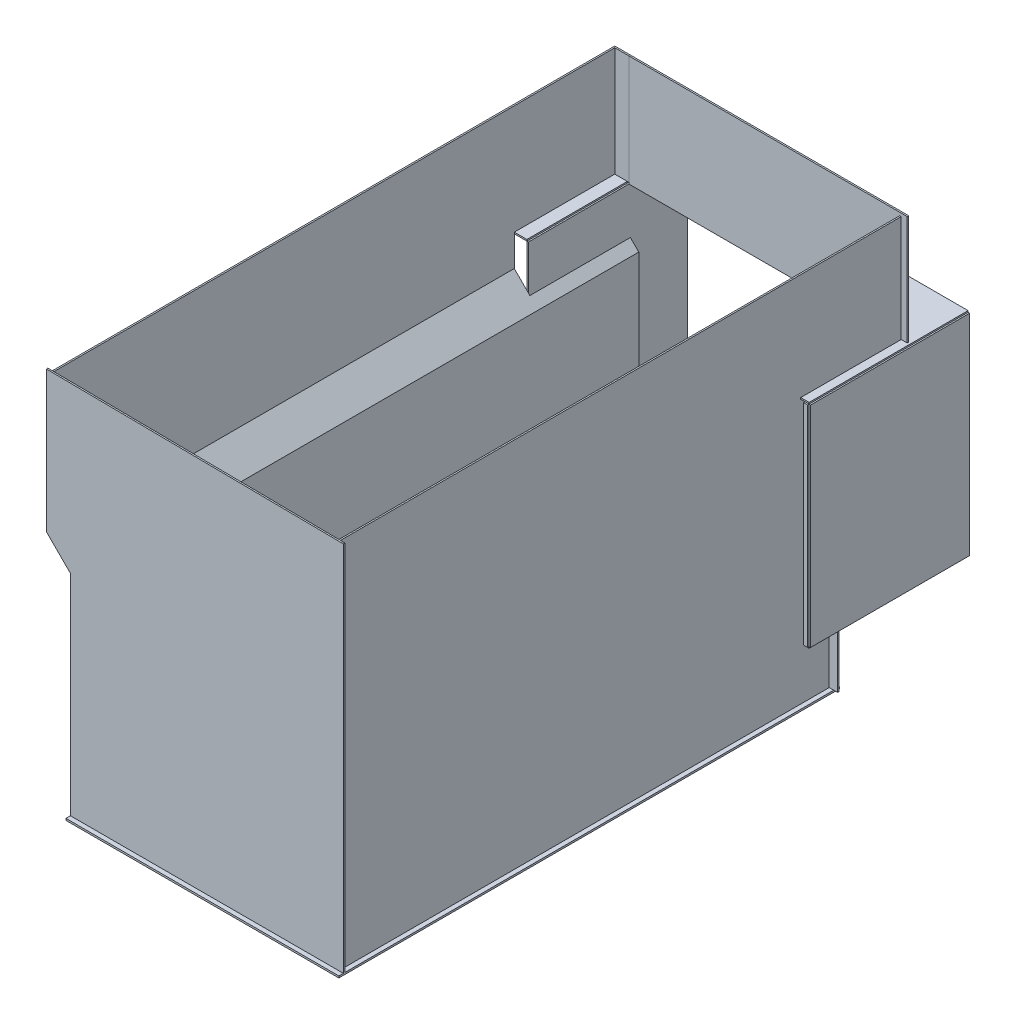
SolidWorks part; units mm, degrees
ref_plane "Front Plane" through (0, 0, 0) normal (0, 0, 1) x (1, 0, 0)
ref_plane "Top Plane" through (0, 0, 0) normal (0, 1, 0) x (1, 0, 0)
ref_plane "Right Plane" through (0, 0, 0) normal (1, 0, 0) x (0, 0, -1)
sketch "Sketch1" plane through (0, 0, 0) normal (0, 0, 1) x (1, 0, 0)
  line L0 (-2072.4189, 0) -> (1450.1392, 0) construction
  line L1 (0, 1209.3329) -> (0, -1426.529) construction
  line L9 (455, 482.6106) -> (455, -757.3894)
  line L10 (455, -757.3894) -> (-455, -757.3894)
  line L11 (-455, -757.3894) -> (-455, -57.3894)
  line L12 (-455, -57.3894) -> (-535, 22.6106)
  line L13 (-535, 22.6106) -> (-535, 492.6106)
  line L14 (-535, 492.6106) -> (455, 482.6106)
  dimension "D1" = 1240
  dimension "D2" = 1250
  dimension "D3" = 910
  dimension "D4" = 990
  dimension "D5" = 700
  dimension "D6" = 80
  dimension "D7" = 80
  dimension "D8" = 470
  dimension "D13" = 455
extrude "Boss-Extrude1" add sketch "Sketch1" along normal blind 5
sketch "Sketch2" plane through (0, -757.3894, 0) normal (0, -1, 0) x (-1, 0, 0)
  line L0 (455, -20) -> (-455, -20)
  line L1 (-455, -20) -> (-455, 1650)
  line L2 (-455, 1650) -> (455, 1650)
  line L3 (455, 1650) -> (455, -20)
  line L4 (535, -5) -> (455, -5) construction
  dimension "D1" = 910
  dimension "D2" = 455
  dimension "D3" = 1670
  dimension "D4" = 15
extrude "Boss-Extrude2" add sketch "Sketch2" along normal blind 6
sketch "Sketch3" plane through (0, 0, 0) normal (0, 0, -1) x (-1, 0, 0)
  line L2 (435, -757.3894) -> (435, -57.3894)
  line L3 (435, -57.3894) -> (515, 22.6106)
  line L4 (515, 22.6106) -> (515, 492.6106)
  line L6 (440, -757.3894) -> (440, -59.4605)
  line L7 (440, -59.4605) -> (520, 20.5395)
  line L8 (520, 20.5395) -> (520, 492.6106)
  line L9 (515, 492.6106) -> (520, 492.6106)
  line L10 (440, -757.3894) -> (435, -757.3894)
  line L12 (455, -757.3894) -> (-455, -757.3894) construction
  line L15 (-440, 482.6106) -> (-435, 482.6106)
  line L16 (-440, 482.6106) -> (-440, -757.3894)
  line L17 (-440, -757.3894) -> (-435, -757.3894)
  line L18 (-435, 482.6106) -> (-435, -757.3894)
  dimension "D1" = 5
  dimension "D2" = 1250
  dimension "D3" = 700
  dimension "D4" = 80
  dimension "D5" = 80
  dimension "D6" = 0
  dimension "D7" = 435
  dimension "D8" = 1240
  dimension "D9" = 0
  dimension "D10" = 5
  dimension "D11" = 435
extrude "Boss-Extrude3" add sketch "Sketch3" along normal blind 1870
sketch "Sketch4" plane through (0, 0, 0) normal (1, 0, 0) x (0, 0, -1)
  line L0 (1630, -757.3894) -> (1630, -577.3894)
  line L1 (1650, -757.3894) -> (0, -757.3894) construction
  line L2 (1630, -577.3894) -> (2060, -577.3894)
  line L4 (2060, 122.6106) -> (1870, 122.6106)
  line L5 (1870, 122.6106) -> (1870, 492.6106)
  line L7 (815, 588.8415) -> (815, -1128.6828) construction
  line L8 (0, -757.3894) -> (0, 482.6106) construction
  line L13 (1630, -757.3894) -> (1635, -757.3894)
  line L14 (1635, -757.3894) -> (1635, -582.3894)
  line L15 (1635, -582.3894) -> (2065, -582.3894)
  line L17 (2065, 127.6106) -> (1875, 127.6106)
  line L18 (1875, 127.6106) -> (1875, 492.6106)
  line L20 (1870, 482.6106) -> (1870, -757.3894) construction
  line L21 (1875, 492.6106) -> (1870, 492.6106)
  line L22 (1688.4853, -227.3894) -> (2285.3749, -227.3894) construction
  line L23 (1650, -757.3894) -> (0, -757.3894) construction
  line L24 (2060, 122.6106) -> (2065, 122.6106)
  line L25 (2065, 122.6106) -> (2065, 127.6106)
  line L26 (2065, -582.3894) -> (2065, -577.3894)
  line L27 (2065, -577.3894) -> (2060, -577.3894)
  dimension "D1" = 180
  dimension "D3" = 815
  dimension "D5" = 815
  dimension "D6" = 5
  dimension "D7" = 5
  dimension "D9" = 5
  dimension "D10" = 5
  dimension "D11" = 0
  dimension "D12" = 1250
  dimension "D13" = 700
  dimension "D14" = 350
  dimension "D15" = 530
extrude "Boss-Extrude4" add sketch "Sketch4" along normal mid plane 936
sketch "Sketch5" plane through (440, 0, 0) normal (1, 0, 0) x (0, 0, -1)
  line L0 (1635, -582.3894) -> (1870, -582.3894)
  line L1 (1870, -582.3894) -> (1870, -757.3894)
  line L2 (1870, -757.3894) -> (1635, -757.3894)
  line L3 (1635, -757.3894) -> (1635, -582.3894)
extrude "Cut-Extrude1" cut sketch "Sketch5" against normal through all both and the other way through all
sketch "Sketch7" plane through (468, 0, 0) normal (1, 0, 0) x (0, 0, -1)
  line L0 (2065, 122.6106) -> (1535, 122.6106)
  line L1 (1535, 122.6106) -> (1535, -577.3894)
  line L2 (2065, -577.3894) -> (1535, -577.3894)
  line L3 (1870, 482.6106) -> (1870, 122.6106) construction
  line L4 (2065, 122.6106) -> (2065, -577.3894)
  dimension "D1" = 195
  dimension "D2" = 530
  dimension "D3" = 700
extrude "Boss-Extrude5" add sketch "Sketch7" along normal blind 5 separate body
sketch "Sketch8" plane through (-468, 0, 0) normal (-1, 0, 0) x (0, 0, 1)
  line L0 (-2065, -577.3894) -> (-1535, -577.3894)
  line L1 (-1535, -577.3894) -> (-2065, -577.3894) construction
  line L2 (-1535, -577.3894) -> (-1535, 122.6106)
  line L3 (-2065, 122.6106) -> (-1535, 122.6106)
  line L4 (-1870, 492.6106) -> (-1870, 122.6106) construction
  line L5 (-1870, 20.5395) -> (-1870, 492.6106) construction
  line L6 (0, -757.3894) -> (-1630, -757.3894) construction
  line L7 (-2065, 122.6106) -> (-2065, -577.3894)
  dimension "D1" = 195
  dimension "D2" = 335
  dimension "D3" = 180
  dimension "D4" = 530
  dimension "D5" = 700
extrude "Boss-Extrude9" add sketch "Sketch8" along normal blind 5 separate body
sketch "Sketch9" plane through (-468, 0, 0) normal (-1, 0, 0) x (0, 0, 1)
  line L0 (-2065, -577.3894) -> (-1535, -577.3894) construction
  line L1 (-2065, -577.3894) -> (-1635, -577.3894)
  line L2 (-2065, -577.3894) -> (-2065, -582.3894)
  line L3 (-2065, -582.3894) -> (-1635, -582.3894)
  line L4 (-1635, -577.3894) -> (-1635, -582.3894)
  line L5 (-2065, 122.6106) -> (-2065, -577.3894) construction
  line L6 (-1635, -582.3894) -> (-2065, -582.3894) construction
  line L7 (-1635, -757.3894) -> (-1635, -582.3894) construction
extrude "Boss-Extrude12" add sketch "Sketch9" along normal blind 15 separate body
sketch "Sketch10" plane through (0, 122.6106, 0) normal (0, 1, 0) x (1, 0, 0)
  line L0 (-515, 1870) -> (-515, 0) construction
  line L1 (468, 1535) -> (440, 1535)
  line L2 (468, 1535) -> (468, 1870)
  line L3 (468, 1870) -> (440, 1870)
  line L4 (440, 1535) -> (440, 1870)
  line L5 (-515, 1870) -> (-473, 1870)
  line L6 (-515, 1870) -> (-515, 1535)
  line L7 (-515, 1535) -> (-473, 1535)
  line L8 (-473, 1870) -> (-473, 1535)
  line L9 (-515, 1870) -> (-435, 1870) construction
  dimension "D1" = 28
  dimension "D2" = 335
  dimension "D3" = 335
  dimension "D4" = 42
extrude "Boss-Extrude13" add sketch "Sketch10" along normal blind 5 separate body
sketch "Sketch11" plane through (0, 0, -1870) normal (0, 0, 1) x (1, 0, 0)
  line L0 (455, -757.3894) -> (455, 482.6106) construction
  line L1 (468, 127.6106) -> (460, 127.6106)
  line L2 (468, 127.6106) -> (468, 499.1119)
  line L3 (468, 499.1119) -> (460, 499.1119)
  line L4 (460, 127.6106) -> (460, 499.1119)
  dimension "D1" = 5
extrude "Cut-Extrude2" cut sketch "Sketch11" against normal blind 5
sketch "Sketch12" plane through (-473, 0, 0) normal (-1, 0, 0) x (0, 0, 1)
  line L0 (-1535, 122.6106) -> (-2065, 122.6106) construction
  line L1 (-1890.5162, 122.6106) -> (-1535, 122.6106)
  line L2 (-1890.5162, 122.6106) -> (-1890.5162, -41.1944)
  line L3 (-1890.5162, -41.1944) -> (-1535, -41.1944)
  line L4 (-1535, 122.6106) -> (-1535, -41.1944)
  line L5 (-1535, -577.3894) -> (-1535, 122.6106) construction
extrude "Cut-Extrude3" cut sketch "Sketch12" along normal blind 237 and the other way blind 10
sketch "Sketch13" plane through (0, 0, -1535) normal (0, 0, 1) x (1, 0, 0)
  line L0 (455, -757.3894) -> (455, 482.6106) construction
  line L1 (455, 122.6106) -> (468, 122.6106)
  line L2 (455, 122.6106) -> (455, -577.3894)
  line L3 (455, -577.3894) -> (468, -577.3894)
  line L4 (468, 122.6106) -> (468, -577.3894)
  line L5 (468, 122.6106) -> (440, 122.6106) construction
extrude "Boss-Extrude14" add sketch "Sketch13" along normal blind 5
sketch "Sketch14" plane through (0, -577.3894, 0) normal (0, -1, 0) x (-1, 0, 0)
  line L1 (-468, 1630) -> (-455, 1630)
  line L2 (-468, 1630) -> (-468, 1535)
  line L3 (-468, 1535) -> (-455, 1535)
  line L4 (-455, 1630) -> (-455, 1535)
extrude "Boss-Extrude15" add sketch "Sketch14" along normal blind 5
sketch "Sketch15" plane through (0, 0, -1535) normal (0, 0, 1) x (1, 0, 0)
  line L0 (-468, -577.3894) -> (-468, 122.6106) construction
  line L1 (-468, -577.3894) -> (-455, -577.3894)
  line L2 (-468, -577.3894) -> (-468, -57.3894)
  line L4 (-455, -577.3894) -> (-455, -57.3894)
  line L5 (-535, 22.6106) -> (-455, -57.3894) construction
  line L6 (-468, -44.3894) -> (-455, -44.3894)
  line L7 (-468, -44.3894) -> (-468, -57.3894)
  line L9 (-455, -44.3894) -> (-455, -57.3894)
extrude "Boss-Extrude16" add sketch "Sketch15" along normal blind 5
sketch "Sketch16" plane through (0, -577.3894, 0) normal (0, -1, 0) x (1, 0, 0)
  line L1 (-463, -1535) -> (-468, -1535)
  line L2 (-463, -1535) -> (-463, -1630)
  line L3 (-463, -1630) -> (-468, -1630)
  line L4 (-468, -1535) -> (-468, -1630)
extrude "Boss-Extrude18" add sketch "Sketch16" along normal blind 5 separate body contours L2 L3 L4 L1
sketch "Sketch17" plane through (0, 0, -1870) normal (0, 0, -1) x (-1, 0, 0)
  line L1 (520, 492.6106) -> (468, 492.6106)
  line L2 (520, 492.6106) -> (520, 127.6106)
  line L3 (520, 127.6106) -> (468, 127.6106)
  line L4 (468, 492.6106) -> (468, 127.6106)
extrude "Boss-Extrude20" add sketch "Sketch17" along normal blind 5 separate body contours L3 L4 L1 L2
ref_plane "Plane1" through (940, 0, 0) normal (1, 0, 0) x (0, 0, -1)
ref_plane "Plane2" through (0, 0, -2875) normal (0, 0, -1) x (-1, 0, 0)
